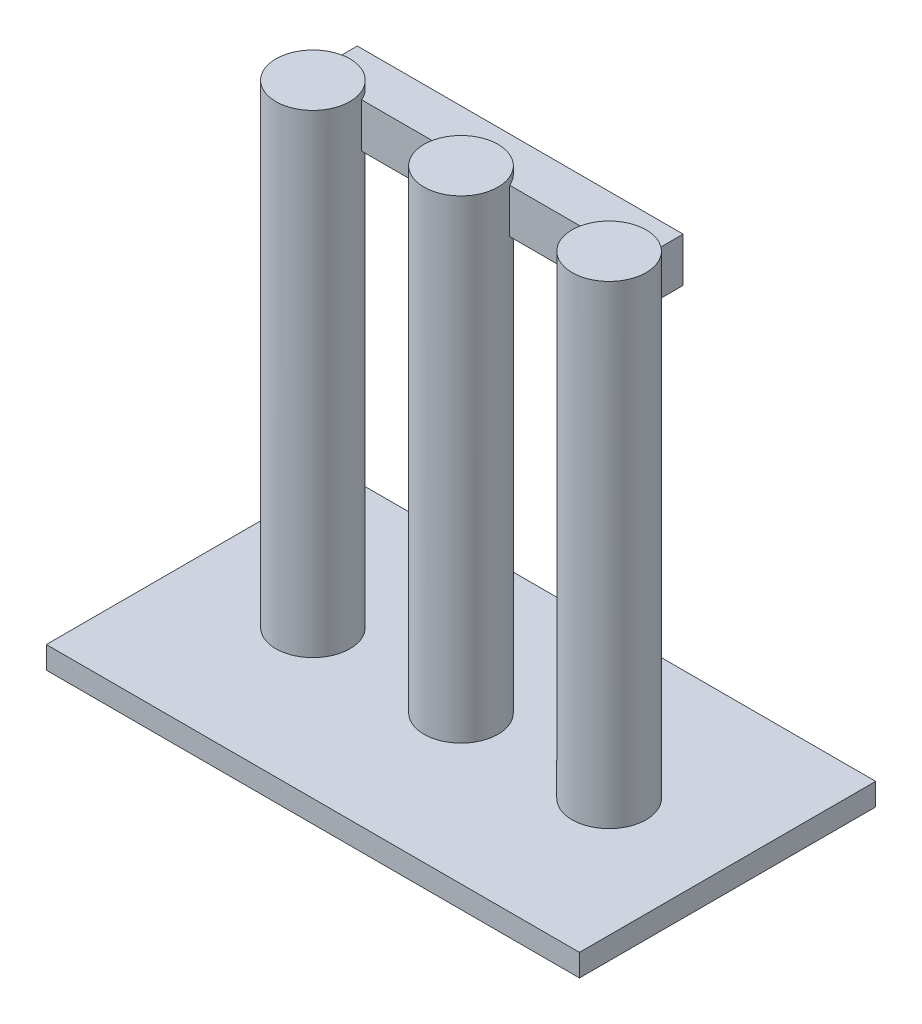
SolidWorks part; units mm, degrees
ref_plane "Front Plane" through (0, 0, 0) normal (0, 0, 1) x (1, 0, 0)
ref_plane "Top Plane" through (0, 0, 0) normal (0, 1, 0) x (1, 0, 0)
ref_plane "Right Plane" through (0, 0, 0) normal (1, 0, 0) x (0, 0, -1)
other "Configuration Table"
sketch "Sketch1" plane through (0, 0, 0) normal (0, 1, 0) x (1, 0, 0)
  line L1 (-7300, 3000) -> (-3700, 3000)
  line L2 (-7300, 3000) -> (-7300, 5000)
  line L3 (-7300, 5000) -> (-3700, 5000)
  line L4 (-3700, 3000) -> (-3700, 5000)
extrude "Boss-Extrude1" add sketch "Sketch1" along normal blind 150
sketch "Sketch2" plane through (0, 0, 0) normal (0, 1, 0) x (1, 0, 0)
  circle A0 centre (-6500, 4000) radius 250
extrude "Boss-Extrude2" add sketch "Sketch2" along normal blind 3200 from offset 150
sketch "Sketch3" plane through (0, 0, 0) normal (0, 1, 0) x (1, 0, 0)
  circle A0 centre (-5500, 4000) radius 250
extrude "Boss-Extrude3" add sketch "Sketch3" along normal blind 3200 from offset 150
sketch "Sketch4" plane through (0, 0, 0) normal (0, 1, 0) x (1, 0, 0)
  circle A0 centre (-4500, 4000) radius 250
extrude "Boss-Extrude4" add sketch "Sketch4" along normal blind 3200 from offset 150
sketch "Sketch5" plane through (0, 0, 0) normal (0, 1, 0) x (1, 0, 0)
  line L1 (-6600, 4100) -> (-4400, 4100)
  line L2 (-6600, 4100) -> (-6600, 4400)
  line L3 (-6600, 4400) -> (-4400, 4400)
  line L4 (-4400, 4100) -> (-4400, 4400)
extrude "Boss-Extrude5" add sketch "Sketch5" along normal blind 300 from offset 3000
